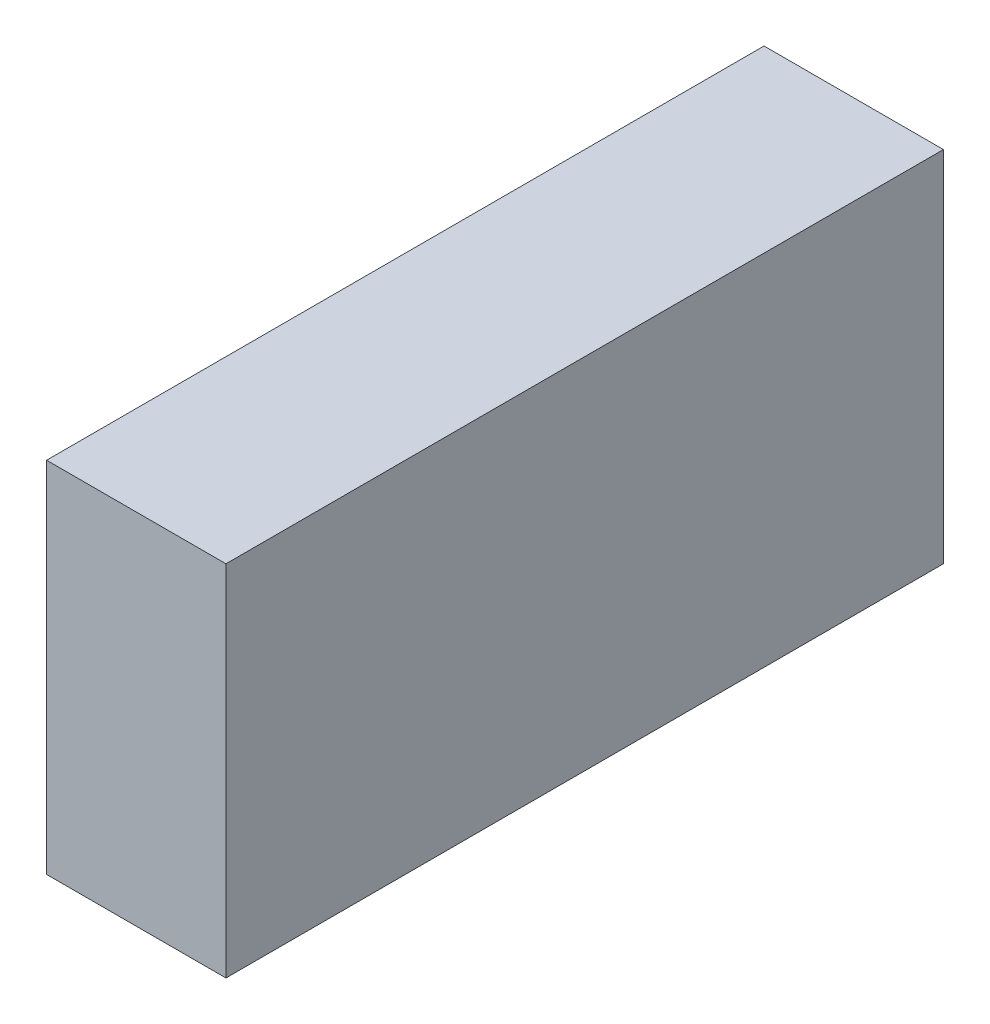
SolidWorks part; units mm, degrees
ref_plane "Front Plane" through (0, 0, 0) normal (0, 0, 1) x (1, 0, 0)
ref_plane "Top Plane" through (0, 0, 0) normal (0, 1, 0) x (1, 0, 0)
ref_plane "Right Plane" through (0, 0, 0) normal (1, 0, 0) x (0, 0, -1)
sketch "Sketch1" plane through (0, 0, 0) normal (0, 0, 1) x (1, 0, 0)
  line L1 (-3.175, 9.525) -> (3.175, 9.525)
  line L2 (-3.175, 9.525) -> (-3.175, 22.225)
  line L3 (-3.175, 22.225) -> (3.175, 22.225)
  line L4 (3.175, 9.525) -> (3.175, 22.225)
  line L5 (-3.175, 9.525) -> (3.175, 22.225) construction
  line L6 (-3.175, 22.225) -> (3.175, 9.525) construction
  circle A0 centre (0, 0) radius 15.875 construction
  point P3 (0, 15.875)
  dimension "D1" = 31.75
  dimension "D2" = 6.35
  dimension "D3" = 12.7
extrude "Boss-Extrude1" add sketch "Sketch1" along normal mid plane 25.4
